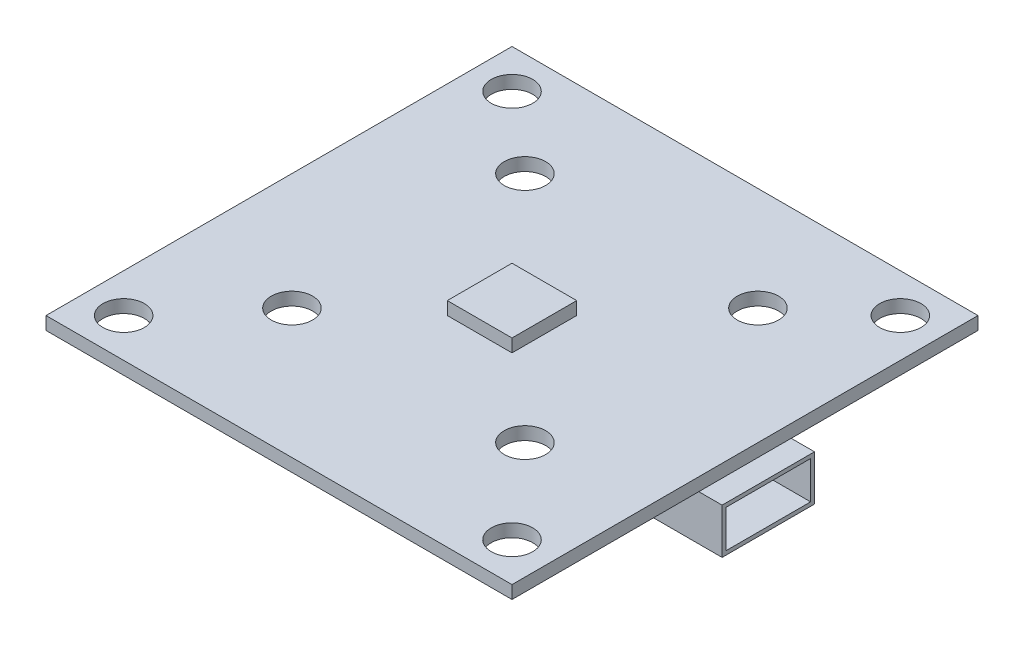
SolidWorks part; units mm, degrees
ref_plane "Front Plane" through (0, 0, 0) normal (0, 0, 1) x (1, 0, 0)
ref_plane "Top Plane" through (0, 0, 0) normal (0, 1, 0) x (1, 0, 0)
ref_plane "Right Plane" through (0, 0, 0) normal (1, 0, 0) x (0, 0, -1)
sketch "Sketch1" plane through (0, 0, 0) normal (0, 1, 0) x (1, 0, 0)
  line L0 (-18, -18) -> (18, 18) construction
  line L1 (-18, 18) -> (18, 18)
  line L2 (-18, 18) -> (-18, -18)
  line L3 (-18, -18) -> (18, -18)
  line L4 (18, 18) -> (18, -18)
  dimension "D1" = 36
  dimension "D2" = 36
extrude "Extrude1" add sketch "Sketch1" along normal blind 1
sketch "Sketch2" plane through (0, 1, 0) normal (0, 1, 0) x (1, 0, 0)
  line L0 (0, 18) -> (0, 15.3854) construction
  line L1 (18, 18) -> (-18, 18) construction
  line L2 (18, 0) -> (14.7707, 0) construction
  line L3 (18, -18) -> (18, 18) construction
  line L4 (18, 1) -> (12.8007, 1) construction
  line L5 (-18, -18) -> (18, -18) construction
  circle A0 centre (-15, 15) radius 1.6
  circle A1 centre (15, 15) radius 1.6
  circle A2 centre (15, -15) radius 1.6
  circle A3 centre (-15, -15) radius 1.6
  circle A4 centre (-9, 10) radius 1.6
  circle A5 centre (9, 10) radius 1.6
  circle A6 centre (9, -8) radius 1.6
  circle A7 centre (-9, -8) radius 1.6
  dimension "D1" = 3.2
  dimension "D2" = 30
  dimension "D3" = 30
  dimension "D4" = 18
  dimension "D5" = 10
  dimension "D6" = 18
extrude "Extrude2" cut sketch "Sketch2" against normal through all
ref_plane "Plane1" through (0, 0, 0) normal (0, 0, 1) x (1, 0, 0)
sketch "Sketch5" plane through (0, 1, 0) normal (0, 1, 0) x (1, 0, 0)
  line L0 (-2.5, -2.5) -> (2.5, 2.5) construction
  line L1 (-2.5, 2.5) -> (2.5, 2.5)
  line L2 (-2.5, 2.5) -> (-2.5, -2.5)
  line L3 (-2.5, -2.5) -> (2.5, -2.5)
  line L4 (2.5, 2.5) -> (2.5, -2.5)
  dimension "D1" = 5
  dimension "D2" = 5
extrude "Extrude5" add sketch "Sketch5" along normal blind 1 separate body
sketch "Sketch10" plane through (0, 0, 0) normal (0, -1, 0) x (1, 0, 0)
  line L0 (0, 0) -> (11.8364, 0) construction
  line L1 (19.8, 3.5688) -> (11.8364, 3.5688)
  line L2 (19.8, 3.5688) -> (19.8, -3.5688)
  line L3 (19.8, -3.5688) -> (11.8364, -3.5688)
  line L4 (11.8364, 3.5688) -> (11.8364, -3.5688)
  line L5 (18, 18) -> (18, -18) construction
  dimension "D1" = 1.8
extrude "Extrude7" add sketch "Sketch10" along normal blind 3.5 separate body
shell "Shell1" thickness 0.3
